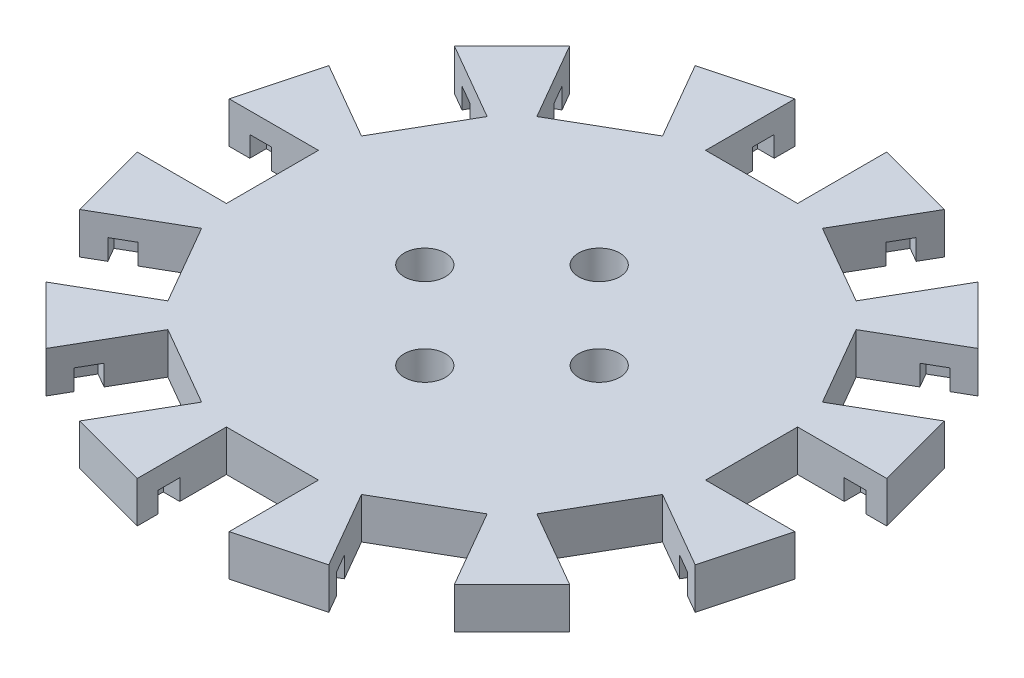
SolidWorks part; units mm, degrees
ref_plane "Front Plane" through (0, 0, 0) normal (0, 0, 1) x (1, 0, 0)
ref_plane "Top Plane" through (0, 0, 0) normal (0, 1, 0) x (1, 0, 0)
ref_plane "Right Plane" through (0, 0, 0) normal (1, 0, 0) x (0, 0, -1)
sketch "Sketch2" plane through (0, 0, 0) normal (0, 1, 0) x (1, 0, 0)
  line L1 (0, 24.8466) -> (-12.4233, 21.5178)
  line L2 (-12.4233, 21.5178) -> (-21.5178, 12.4233)
  line L3 (-21.5178, 12.4233) -> (-24.8466, 0)
  line L4 (-24.8466, 0) -> (-21.5178, -12.4233)
  line L5 (-21.5178, -12.4233) -> (-12.4233, -21.5178)
  line L6 (-12.4233, -21.5178) -> (0, -24.8466)
  line L7 (0, -24.8466) -> (12.4233, -21.5178)
  line L8 (12.4233, -21.5178) -> (21.5178, -12.4233)
  line L9 (21.5178, -12.4233) -> (24.8466, 0)
  line L10 (24.8466, 0) -> (21.5178, 12.4233)
  line L11 (21.5178, 12.4233) -> (12.4233, 21.5178)
  line L12 (12.4233, 21.5178) -> (0, 24.8466)
  circle A0 centre (0, 0) radius 24 construction
  dimension "D1" = 48
extrude "Boss-Extrude1" add sketch "Sketch2" along normal blind 3
sketch "Sketch3" plane through (0, 3, 0) normal (0, 1, 0) x (1, 0, 0)
  line L0 (-3.35, 23.949) -> (0, 24.8466)
  line L1 (0, 24.8466) -> (-12.4233, 21.5178) construction
  line L2 (0, 24.8466) -> (3.35, 23.949)
  line L3 (12.4233, 21.5178) -> (0, 24.8466) construction
  line L4 (3.35, 23.949) -> (3.35, 17.449)
  line L5 (3.35, 17.449) -> (-3.35, 17.449)
  line L6 (-3.35, 17.449) -> (-3.35, 23.949)
  line L7 (5.8233, 16.7863) -> (9.0733, 22.4154)
  line L8 (9.0733, 22.4154) -> (12.4233, 21.5178)
  line L9 (12.4233, 21.5178) -> (14.8757, 19.0654)
  line L10 (14.8757, 19.0654) -> (11.6257, 13.4363)
  line L11 (11.6257, 13.4363) -> (5.8233, 16.7863)
  line L12 (13.4363, 11.6257) -> (19.0654, 14.8757)
  line L13 (19.0654, 14.8757) -> (21.5178, 12.4233)
  line L14 (21.5178, 12.4233) -> (22.4154, 9.0733)
  line L15 (22.4154, 9.0733) -> (16.7863, 5.8233)
  line L16 (16.7863, 5.8233) -> (13.4363, 11.6257)
  line L17 (17.449, 3.35) -> (23.949, 3.35)
  line L18 (23.949, 3.35) -> (24.8466, 0)
  line L19 (24.8466, 0) -> (23.949, -3.35)
  line L20 (23.949, -3.35) -> (17.449, -3.35)
  line L21 (17.449, -3.35) -> (17.449, 3.35)
  line L22 (16.7863, -5.8233) -> (22.4154, -9.0733)
  line L23 (22.4154, -9.0733) -> (21.5178, -12.4233)
  line L24 (21.5178, -12.4233) -> (19.0654, -14.8757)
  line L25 (19.0654, -14.8757) -> (13.4363, -11.6257)
  line L26 (13.4363, -11.6257) -> (16.7863, -5.8233)
  line L27 (11.6257, -13.4363) -> (14.8757, -19.0654)
  line L28 (14.8757, -19.0654) -> (12.4233, -21.5178)
  line L29 (12.4233, -21.5178) -> (9.0733, -22.4154)
  line L30 (9.0733, -22.4154) -> (5.8233, -16.7863)
  line L31 (5.8233, -16.7863) -> (11.6257, -13.4363)
  line L32 (3.35, -17.449) -> (3.35, -23.949)
  line L33 (3.35, -23.949) -> (0, -24.8466)
  line L34 (0, -24.8466) -> (-3.35, -23.949)
  line L35 (-3.35, -23.949) -> (-3.35, -17.449)
  line L36 (-3.35, -17.449) -> (3.35, -17.449)
  line L37 (-5.8233, -16.7863) -> (-9.0733, -22.4154)
  line L38 (-9.0733, -22.4154) -> (-12.4233, -21.5178)
  line L39 (-12.4233, -21.5178) -> (-14.8757, -19.0654)
  line L40 (-14.8757, -19.0654) -> (-11.6257, -13.4363)
  line L41 (-11.6257, -13.4363) -> (-5.8233, -16.7863)
  line L42 (-13.4363, -11.6257) -> (-19.0654, -14.8757)
  line L43 (-19.0654, -14.8757) -> (-21.5178, -12.4233)
  line L44 (-21.5178, -12.4233) -> (-22.4154, -9.0733)
  line L45 (-22.4154, -9.0733) -> (-16.7863, -5.8233)
  line L46 (-16.7863, -5.8233) -> (-13.4363, -11.6257)
  line L47 (-17.449, -3.35) -> (-23.949, -3.35)
  line L48 (-23.949, -3.35) -> (-24.8466, 0)
  line L49 (-24.8466, 0) -> (-23.949, 3.35)
  line L50 (-23.949, 3.35) -> (-17.449, 3.35)
  line L51 (-17.449, 3.35) -> (-17.449, -3.35)
  line L52 (-16.7863, 5.8233) -> (-22.4154, 9.0733)
  line L53 (-22.4154, 9.0733) -> (-21.5178, 12.4233)
  line L54 (-21.5178, 12.4233) -> (-19.0654, 14.8757)
  line L55 (-19.0654, 14.8757) -> (-13.4363, 11.6257)
  line L56 (-13.4363, 11.6257) -> (-16.7863, 5.8233)
  line L57 (-11.6257, 13.4363) -> (-14.8757, 19.0654)
  line L58 (-14.8757, 19.0654) -> (-12.4233, 21.5178)
  line L59 (-12.4233, 21.5178) -> (-9.0733, 22.4154)
  line L60 (-9.0733, 22.4154) -> (-5.8233, 16.7863)
  line L61 (-5.8233, 16.7863) -> (-11.6257, 13.4363)
  point P10 (17.449, 0)
  point P67 (0, 0)
  point P68 (-17.449, 0)
  dimension "D3" = 12
  dimension "D1" = 6.7
  dimension "D2" = 6.5
extrude "Cut-Extrude1" cut sketch "Sketch3" against normal up to surface (3 mm away) up to face at (0, 0, 0)
sketch "Sketch4" plane through (0, 0, 0) normal (0, -1, 0) x (-1, 0, 0)
  line L4 (3.35, -17.449) -> (-3.35, -17.449) construction
  line L5 (4.55, -20.849) -> (-4.55, -20.849)
  line L6 (4.55, -20.849) -> (4.55, -22.449)
  line L7 (4.55, -22.449) -> (-4.55, -22.449)
  line L8 (-4.55, -20.849) -> (-4.55, -22.449)
  line L9 (4.55, -20.849) -> (-4.55, -22.449) construction
  line L10 (4.55, -22.449) -> (-4.55, -20.849) construction
  line L12 (-6.4841, -20.3308) -> (-7.2841, -21.7164)
  line L13 (-6.4841, -20.3308) -> (-14.3649, -15.7808)
  line L14 (-14.3649, -15.7808) -> (-15.1649, -17.1664)
  line L15 (-7.2841, -21.7164) -> (-15.1649, -17.1664)
  line L16 (-15.7808, -14.3649) -> (-17.1664, -15.1649)
  line L17 (-15.7808, -14.3649) -> (-20.3308, -6.4841)
  line L18 (-20.3308, -6.4841) -> (-21.7164, -7.2841)
  line L19 (-17.1664, -15.1649) -> (-21.7164, -7.2841)
  line L20 (-20.849, -4.55) -> (-22.449, -4.55)
  line L21 (-20.849, -4.55) -> (-20.849, 4.55)
  line L22 (-20.849, 4.55) -> (-22.449, 4.55)
  line L23 (-22.449, -4.55) -> (-22.449, 4.55)
  line L24 (-20.3308, 6.4841) -> (-21.7164, 7.2841)
  line L25 (-20.3308, 6.4841) -> (-15.7808, 14.3649)
  line L26 (-15.7808, 14.3649) -> (-17.1664, 15.1649)
  line L27 (-21.7164, 7.2841) -> (-17.1664, 15.1649)
  line L28 (-14.3649, 15.7808) -> (-15.1649, 17.1664)
  line L29 (-14.3649, 15.7808) -> (-6.4841, 20.3308)
  line L30 (-6.4841, 20.3308) -> (-7.2841, 21.7164)
  line L31 (-15.1649, 17.1664) -> (-7.2841, 21.7164)
  line L32 (-4.55, 20.849) -> (-4.55, 22.449)
  line L33 (-4.55, 20.849) -> (4.55, 20.849)
  line L34 (4.55, 20.849) -> (4.55, 22.449)
  line L35 (-4.55, 22.449) -> (4.55, 22.449)
  line L36 (6.4841, 20.3308) -> (7.2841, 21.7164)
  line L37 (6.4841, 20.3308) -> (14.3649, 15.7808)
  line L38 (14.3649, 15.7808) -> (15.1649, 17.1664)
  line L39 (7.2841, 21.7164) -> (15.1649, 17.1664)
  line L40 (15.7808, 14.3649) -> (17.1664, 15.1649)
  line L41 (15.7808, 14.3649) -> (20.3308, 6.4841)
  line L42 (20.3308, 6.4841) -> (21.7164, 7.2841)
  line L43 (17.1664, 15.1649) -> (21.7164, 7.2841)
  line L44 (20.849, 4.55) -> (22.449, 4.55)
  line L45 (20.849, 4.55) -> (20.849, -4.55)
  line L46 (20.849, -4.55) -> (22.449, -4.55)
  line L47 (22.449, 4.55) -> (22.449, -4.55)
  line L48 (20.3308, -6.4841) -> (21.7164, -7.2841)
  line L49 (20.3308, -6.4841) -> (15.7808, -14.3649)
  line L50 (15.7808, -14.3649) -> (17.1664, -15.1649)
  line L51 (21.7164, -7.2841) -> (17.1664, -15.1649)
  line L52 (14.3649, -15.7808) -> (15.1649, -17.1664)
  line L53 (14.3649, -15.7808) -> (6.4841, -20.3308)
  line L54 (6.4841, -20.3308) -> (7.2841, -21.7164)
  line L55 (15.1649, -17.1664) -> (7.2841, -21.7164)
  point P0 (0, -21.649)
  point P57 (0, 0)
  dimension "D1" = 9.1
  dimension "D2" = 4.2
  dimension "D3" = 1.6
  dimension "D4" = 12
extrude "Cut-Extrude2" cut sketch "Sketch4" against normal blind 1.5
sketch "Sketch5" [suppressed] plane through (0, 0, 0) normal (0, -1, 0) x (-1, 0, 0)
  line L0 (4.55, -22.399) -> (4.55, -20.899) construction
  line L1 (3, -17.649) -> (-3, -17.649)
  line L2 (3, -17.649) -> (3, -25.649)
  line L3 (3, -25.649) -> (-3, -25.649)
  line L4 (-3, -17.649) -> (-3, -25.649)
  line L5 (3, -17.649) -> (-3, -25.649) construction
  line L6 (3, -25.649) -> (-3, -17.649) construction
  line L7 (-3, -19.649) -> (-3.35, -19.649)
  line L8 (-3.35, -17.449) -> (-3.35, -20.899) construction
  line L9 (-3.35, -19.649) -> (-3.35, -23.649)
  line L10 (-3.35, -22.399) -> (-3.35, -23.949) construction
  line L11 (-3.35, -23.649) -> (-3, -23.649)
  line L12 (-3, -23.649) -> (-3, -19.649)
  line L14 (-4.55, -20.899) -> (-4.55, -22.399) construction
  line L15 (0, 0) -> (17.449, 0) construction
  line L16 (17.449, 3.35) -> (17.449, -3.35) construction
  line L17 (3, 25.649) -> (-3, 25.649)
  line L18 (-3, 17.649) -> (-3, 25.649)
  line L19 (3, 17.649) -> (-3, 17.649)
  line L20 (3, 17.649) -> (3, 25.649)
  line L21 (-3.35, 23.649) -> (-3, 23.649)
  line L22 (-3.35, 19.649) -> (-3.35, 23.649)
  line L23 (-3, 19.649) -> (-3.35, 19.649)
  line L24 (-3, 23.649) -> (-3, 19.649)
  point P0 (0, -21.649)
  point P9 (4.55, -21.649)
  point P19 (-4.55, -21.649)
  point P20 (-3.35, -21.649)
  point P26 (17.449, 0)
  dimension "D1" = 8
  dimension "D2" = 6
  dimension "D3" = 4
sketch "Sketch7" plane through (0, 0, 0) normal (0, -1, 0) x (1, 0, 0)
  circle A0 centre (0, 6.35) radius 1.5
  circle A2 centre (6.35, 0) radius 1.5
  circle A3 centre (0, -6.35) radius 1.5
  circle A4 centre (-6.35, 0) radius 1.5
  point P12 (0, 0)
  dimension "D1" = 6.35
  dimension "D2" = 3
  dimension "D3" = 4
extrude "Cut-Extrude4" cut sketch "Sketch7" against normal up to surface (3 mm away) up to face at (0, 3, 0)
sketch "Sketch8" plane through (0, 3, 0) normal (0, 1, 0) x (1, 0, 0)
  circle A0 centre (0, 6.35) radius 3
  circle A1 centre (6.35, 0) radius 3
  circle A2 centre (0, -6.35) radius 3
  circle A3 centre (-6.35, 0) radius 3
  dimension "D1" = 6
extrude "Cut-Extrude5" [suppressed] cut sketch "Sketch8" against normal blind 1.1
